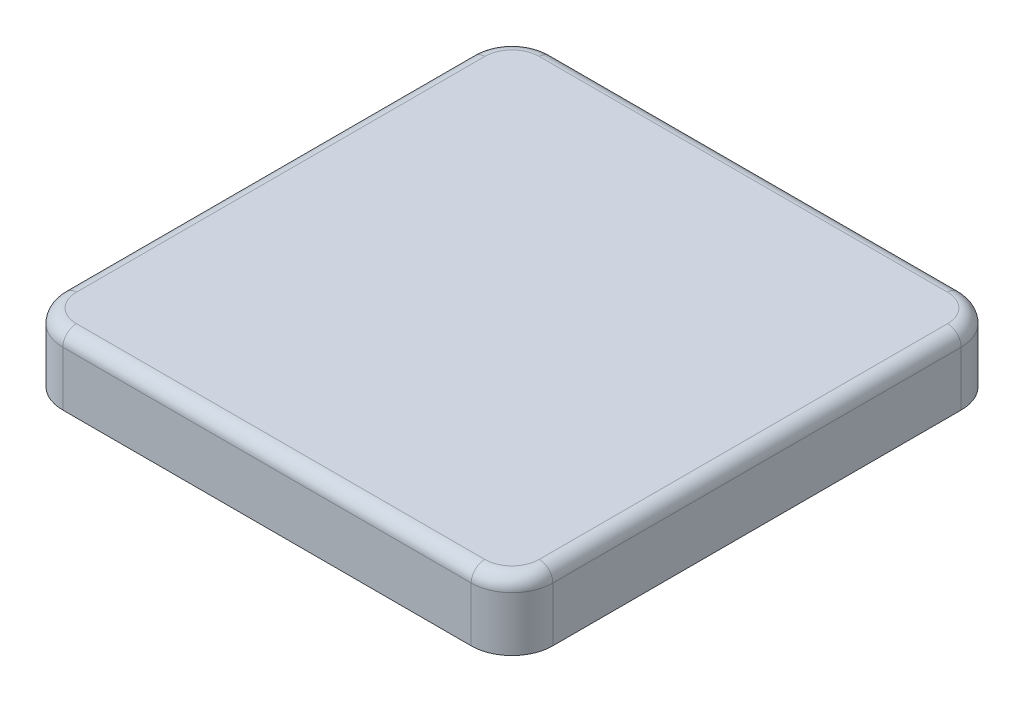
SolidWorks part; units mm, degrees
ref_plane "Front Plane" through (0, 0, 0) normal (0, 0, 1) x (1, 0, 0)
ref_plane "Top Plane" through (0, 0, 0) normal (0, 1, 0) x (1, 0, 0)
ref_plane "Right Plane" through (0, 0, 0) normal (1, 0, 0) x (0, 0, -1)
sketch "Sketch1" plane through (0, 0, 0) normal (0, 1, 0) x (1, 0, 0)
  line L1 (-15, -18) -> (15, -18)
  line L2 (-18, -15) -> (-18, 15)
  line L3 (-15, 18) -> (15, 18)
  line L4 (18, -15) -> (18, 15)
  line L5 (-18, -18) -> (18, 18) construction
  line L6 (-18, 18) -> (18, -18) construction
  arc A0 (-15, -18) -> (-18, -15) centre (-15, -15) cw
  arc A1 (15, -18) -> (18, -15) centre (15, -15) ccw
  arc A2 (15, 18) -> (18, 15) centre (15, 15) cw
  arc A3 (-18, 15) -> (-15, 18) centre (-15, 15) cw
  point P0 (0, 0)
  dimension "D2" = 3
  dimension "D1" = 36
extrude "Boss-Extrude1" add sketch "Sketch1" along normal blind 5
shell "Shell1" thickness 2
fillet "Fillet1" radius 1 8 edges at (-18, 5, 0) (-17.1213, 5, -17.1213) (0, 5, -18) (17.1213, 5, -17.1213) (18, 5, 0) (17.1213, 5, 17.1213) (0, 5, 18) (-17.1213, 5, 17.1213)
sketch "Sketch2" plane through (0, 3, 0) normal (0, -1, 0) x (1, 0, 0)
  circle A0 centre (0, 0) radius 13.5
  dimension "D1" = 27
extrude "Boss-Extrude2" add sketch "Sketch2" along normal up to surface (3 mm away) up to face at (0, 0, 0)
